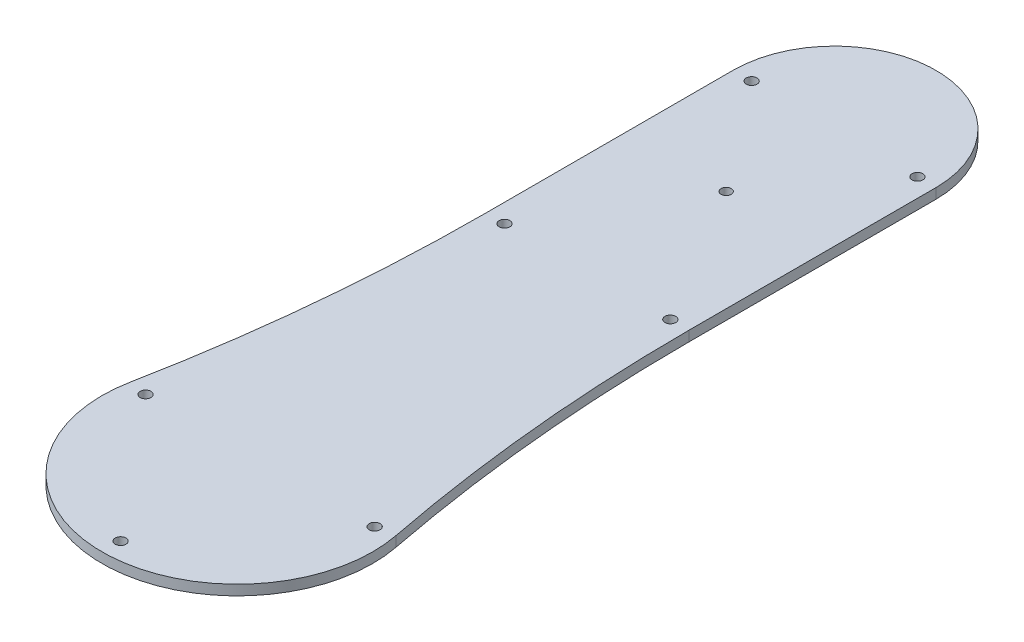
SolidWorks part; units mm, degrees
ref_plane "前视基准面" through (0, 0, 0) normal (0, 0, 1) x (1, 0, 0)
ref_plane "上视基准面" through (0, 0, 0) normal (0, 1, 0) x (1, 0, 0)
ref_plane "右视基准面" through (0, 0, 0) normal (1, 0, 0) x (0, 0, -1)
other "Configuration Table"
sketch "草图1" plane through (0, 0, 0) normal (0, 1, 0) x (1, 0, 0)
  line L0 (30, 176.4575) -> (30, 103.4408)
  line L1 (-30, 176.4575) -> (-30, 103.4408)
  arc A0 (-39.2593, 7.6623) -> (39.2593, 7.6623) centre (0, 0) ccw
  arc A1 (30, 176.4575) -> (-30, 176.4575) centre (0, 176.4575) ccw
  arc A2 (-30, 103.4408) -> (-39.2593, 7.6623) centre (-530, 103.4408) cw
  arc A3 (39.2593, 7.6623) -> (30, 103.4408) centre (530, 103.4408) cw
  dimension "D1" = 80
  dimension "D2" = 500
extrude "凸台-拉伸1" add sketch "草图1" along normal blind 3
sketch "草图2" plane through (0, 3, 0) normal (0, 1, 0) x (1, 0, 0)
  line L0 (0, 0) -> (0, -50000) construction
  circle A0 centre (0, -34.5) radius 1.6
  circle A1 centre (33.8425, 6.7308) radius 1.6
  circle A2 centre (24.5001, 103.4536) radius 1.6
  circle A3 centre (24.5, 176.4689) radius 1.6
  circle A4 centre (-24.5, 176.4689) radius 1.6
  circle A5 centre (-24.5001, 103.4536) radius 1.6
  circle A6 centre (-33.8425, 6.7308) radius 1.6
  dimension "D1" = 3.2
  dimension "D2" = 3.2
  dimension "D3" = 3.2
  dimension "D4" = 3.2
extrude "切除-拉伸1" cut sketch "草图2" against normal blind 3
sketch "草图3" plane through (0, 3, 0) normal (0, 1, 0) x (1, 0, 0)
  circle A0 centre (0, 144.4575) radius 1.5
  point P0 (0, 176.4575)
  point P1 (0.2155, 144.4582)
  point P4 (0, 176.4575)
  dimension "D2" = 3
  dimension "D1" = 32
  dimension "D3" = 32
extrude "切除-拉伸2" cut sketch "草图3" against normal blind 10
